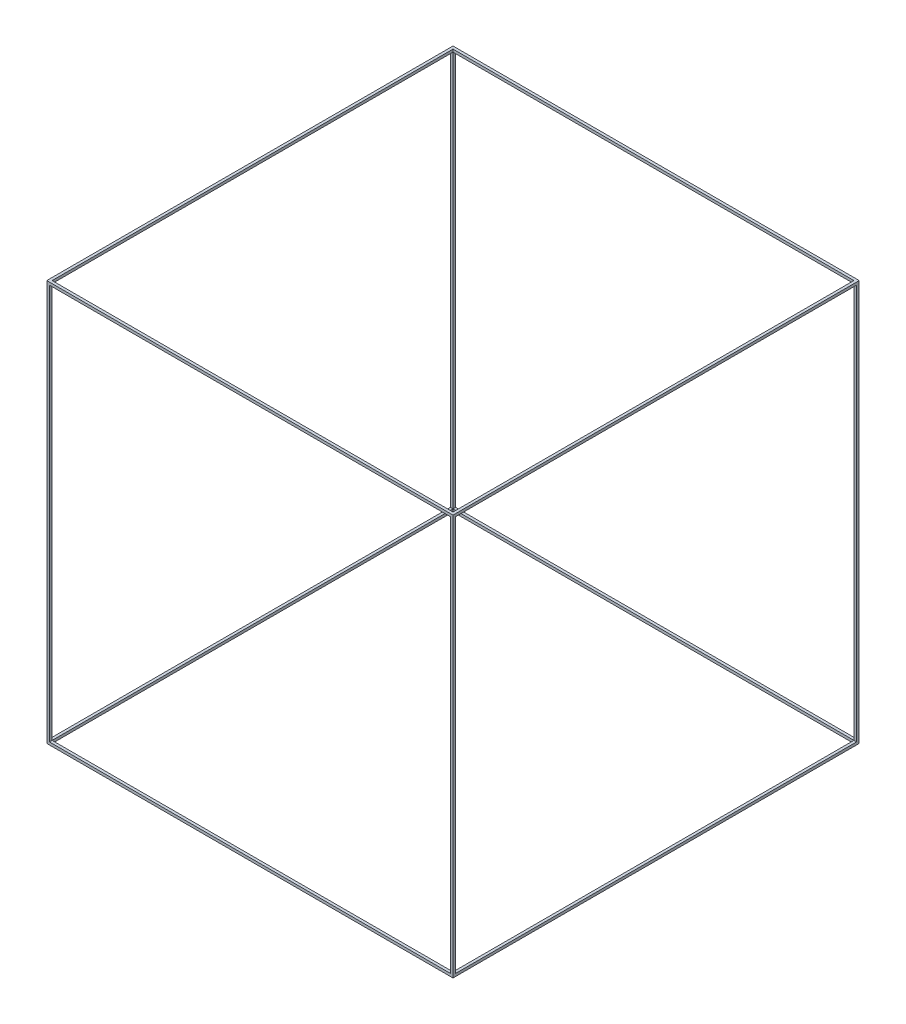
SolidWorks part; units mm, degrees
ref_plane "Front Plane" through (0, 0, 0) normal (0, 0, 1) x (1, 0, 0)
ref_plane "Top Plane" through (0, 0, 0) normal (0, 1, 0) x (1, 0, 0)
ref_plane "Right Plane" through (0, 0, 0) normal (1, 0, 0) x (0, 0, -1)
sketch "Sketch1" plane through (0, 0, 0) normal (0, 1, 0) x (1, 0, 0)
  line L1 (-75, 75) -> (75, 75)
  line L2 (-75, 75) -> (-75, -75)
  line L3 (-75, -75) -> (75, -75)
  line L4 (75, 75) -> (75, -75)
  line L5 (-75, 75) -> (75, -75) construction
  line L6 (-75, -75) -> (75, 75) construction
  point P4 (0, 0)
  point P5 (0, 0)
  dimension "D1" = 150
  dimension "D2" = 150
extrude "Extrude-Thin1" add sketch "Sketch1" along normal blind 150 thin
sketch "Sketch2" plane through (0, 150, 0) normal (0, 1, 0) x (1, 0, 0)
  line L0 (76, -76) -> (76, 76) construction
  line L1 (-75, 75) -> (75, 75)
  line L2 (-75, 75) -> (-75, -75)
  line L3 (-75, -75) -> (75, -75)
  line L4 (75, 75) -> (75, -75)
  line L5 (-75, 75) -> (75, -75) construction
  line L6 (-75, -75) -> (75, 75) construction
  line L7 (-76, -76) -> (76, -76) construction
  line L8 (-76, 76) -> (-76, -76) construction
  line L9 (76, 76) -> (-76, 76) construction
  point P4 (0, 0)
  dimension "D1" = 1
  dimension "D2" = 1
  dimension "D3" = 1
  dimension "D4" = 1
extrude "Cut-Extrude1" cut sketch "Sketch2" against normal blind 152
sketch "Sketch3" plane through (0, 0, 76) normal (0, 0, 1) x (1, 0, 0)
  line L0 (-76, 0) -> (76, 0) construction
  line L1 (-75, 149) -> (75, 149)
  line L2 (-75, 149) -> (-75, 1)
  line L3 (-75, 1) -> (75, 1)
  line L4 (75, 149) -> (75, 1)
  line L5 (-75, 149) -> (75, 1) construction
  line L6 (-75, 1) -> (75, 149) construction
  line L7 (-76, 150) -> (-76, 0) construction
  line L8 (-76, 150) -> (76, 150) construction
  line L9 (76, 150) -> (76, 0) construction
  point P4 (0, 75)
  dimension "D1" = 1
  dimension "D2" = 1
  dimension "D3" = 1
  dimension "D4" = 1
extrude "Cut-Extrude2" cut sketch "Sketch3" against normal blind 152
sketch "Sketch4" plane through (-76, 0, 0) normal (-1, 0, 0) x (0, 0, 1)
  line L0 (-76, 150) -> (76, 150) construction
  line L1 (-75, 149) -> (75, 149)
  line L2 (-75, 149) -> (-75, 1)
  line L3 (-75, 1) -> (75, 1)
  line L4 (75, 149) -> (75, 1)
  line L5 (-75, 149) -> (75, 1) construction
  line L6 (-75, 1) -> (75, 149) construction
  line L7 (76, 150) -> (76, 0) construction
  line L8 (-76, 0) -> (76, 0) construction
  line L9 (-76, 150) -> (-76, 0) construction
  point P4 (0, 75)
  dimension "D1" = 1
  dimension "D2" = 1
  dimension "D3" = 1
  dimension "D4" = 1
extrude "Cut-Extrude3" cut sketch "Sketch4" against normal blind 152
sketch "Sketch5" plane through (0, 1, 0) normal (0, 1, 0) x (1, 0, 0)
  line L1 (-75, 75) -> (75, 75) construction
  line L2 (-75, 75) -> (-75, -75) construction
  line L3 (-75, -75) -> (75, -75) construction
  line L4 (75, 75) -> (75, -75) construction
  line L5 (-75, 75) -> (75, -75) construction
  line L6 (-75, -75) -> (75, 75) construction
  point P4 (0, 0)
